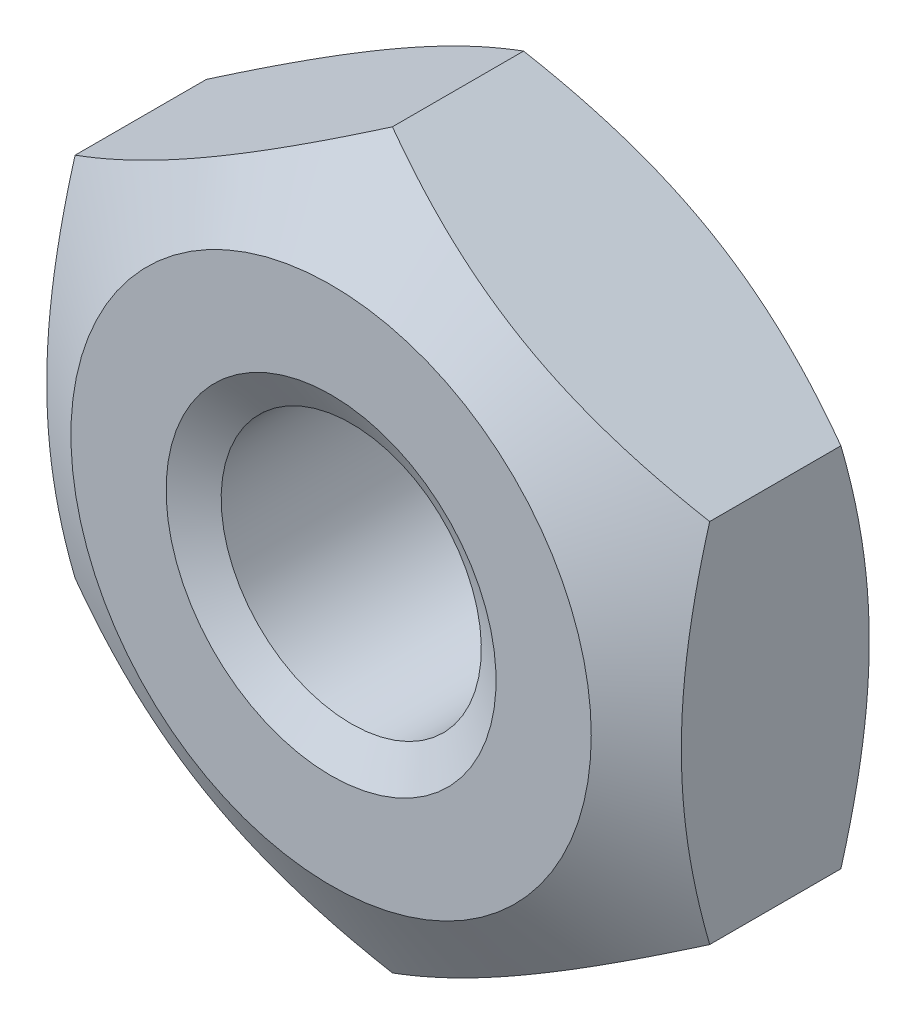
SolidWorks part; units mm, degrees
ref_plane "Front Plane" through (0, 0, 0) normal (0, 0, 1) x (1, 0, 0)
ref_plane "Top Plane" through (0, 0, 0) normal (0, 1, 0) x (1, 0, 0)
ref_plane "Right Plane" through (0, 0, 0) normal (1, 0, 0) x (0, 0, -1)
sketch "Sketch1" plane through (0, 0, 0) normal (0, 0, 1) x (1, 0, 0)
  line L0 (0, 0) -> (0, 2.8868) construction
  line L1 (0, 2.8868) -> (-2.5, 1.4434)
  line L2 (-2.5, 1.4434) -> (-2.5, -1.4434)
  line L3 (-2.5, -1.4434) -> (0, -2.8868)
  line L4 (0, -2.8868) -> (2.5, -1.4434)
  line L5 (2.5, -1.4434) -> (2.5, 1.4434)
  line L6 (2.5, 1.4434) -> (0, 2.8868)
  circle A0 centre (0, 0) radius 2.5 construction
  dimension "S DIM" = 5
extrude "Boss-Extrude1" add sketch "Sketch1" against normal blind 2
sketch "Sketch4" plane through (0, 0, 0) normal (1, 0, 0) x (0, 0, -1)
  line L0 (2, 2.8868) -> (1.5169, 2.8868)
  line L1 (2, 2.8868) -> (0, 2.8868) construction
  line L2 (1.5169, 2.8868) -> (2, 2.05)
  line L4 (2, 2.05) -> (2, 2.8868)
  line L5 (0, 0) -> (3.2979, 0) construction
  line L6 (0, 2.8868) -> (0.4831, 2.8868)
  line L7 (0.4831, 2.8868) -> (0, 2.05)
  line L9 (0, 2.05) -> (0, 2.8868)
  dimension "SAME S 1" = 4.1
  dimension "D2" = 30
  dimension "SAME S 2" = 4.1
  dimension "D4" = 30
revolve "Cut-Revolve1" cut sketch "Sketch4" angle 360 about L5
sketch "Sketch5" plane through (0, 0, 0) normal (1, 0, 0) x (0, 0, -1)
  line L0 (0, 0) -> (2, 0) construction
  line L1 (0, 0) -> (0, 1.3)
  line L2 (0, 2.05) -> (0, -2.05) construction
  line L3 (0, 1.3) -> (0.1588, 1.025)
  line L4 (0.1588, 1.025) -> (1.8412, 1.025)
  line L5 (1.8412, 1.025) -> (2, 1.3)
  line L6 (2, 1.3) -> (2, 0)
  line L8 (2, -2.05) -> (2, 2.05) construction
  line L9 (2, 0) -> (0, 0)
  dimension "D1" = 60
  dimension "D2" = 60
  dimension "Hole2" = 2.6
  dimension "Hole1" = 2.05
revolve "Cut-Revolve2" cut sketch "Sketch5" angle 360 about L0
cosmetic thread "Cosmetic Thread1" parameters "D2"=2.5
